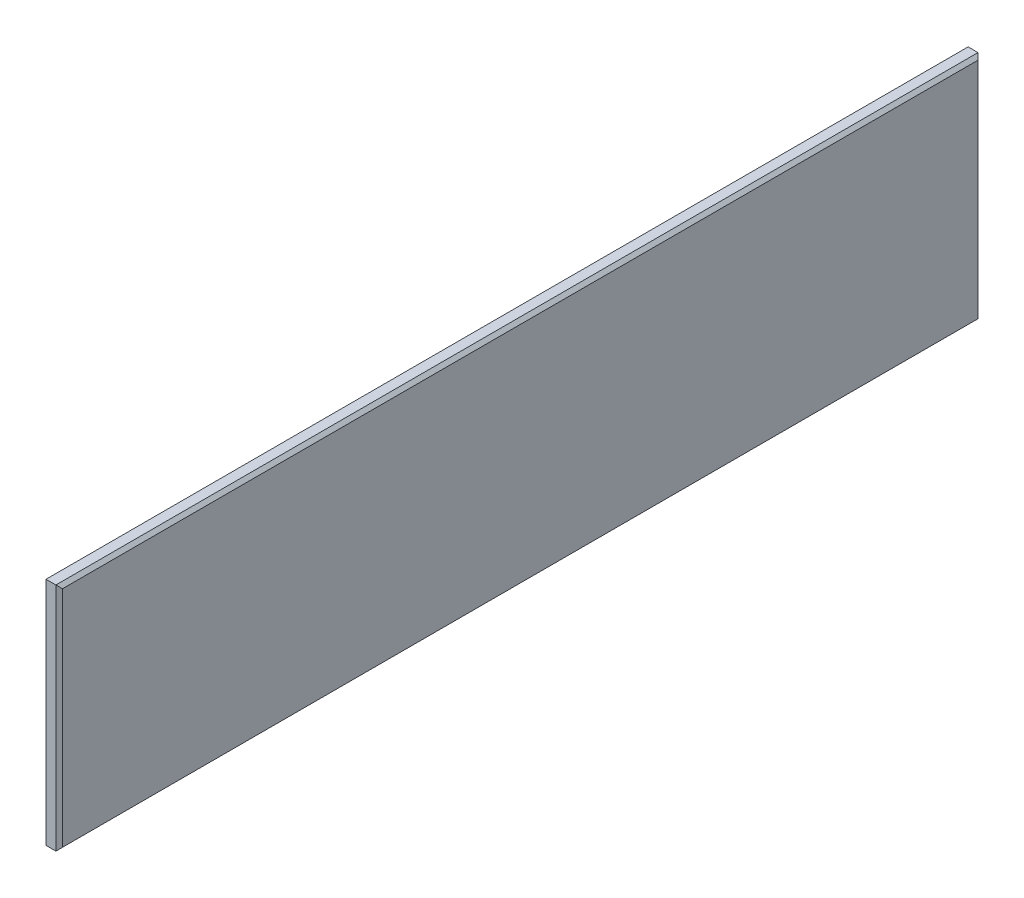
SolidWorks part; units mm, degrees
ref_plane "Front Plane" through (0, 0, 0) normal (0, 0, 1) x (1, 0, 0)
ref_plane "Top Plane" through (0, 0, 0) normal (0, 1, 0) x (1, 0, 0)
ref_plane "Right Plane" through (0, 0, 0) normal (1, 0, 0) x (0, 0, -1)
sketch "Sketch1" plane through (0, 0, 0) normal (0, 1, 0) x (1, 0, 0)
  line L1 (0, 0) -> (5, 0)
  line L2 (0, 0) -> (0, 280)
  line L3 (0, 280) -> (5, 280)
  line L4 (5, 0) -> (5, 280)
  dimension "D1" = 280
  dimension "D2" = 5
extrude "Boss-Extrude1" add sketch "Sketch1" along normal blind 70
chamfer "Chamfer2" distance 1 angle 45 8 edges at (0, 35, -280) (0, 70, -140) (0, 35, 0) (0, 0, -140) (5, 35, 0) (5, 70, -140) (5, 35, -280) (5, 0, -140)
